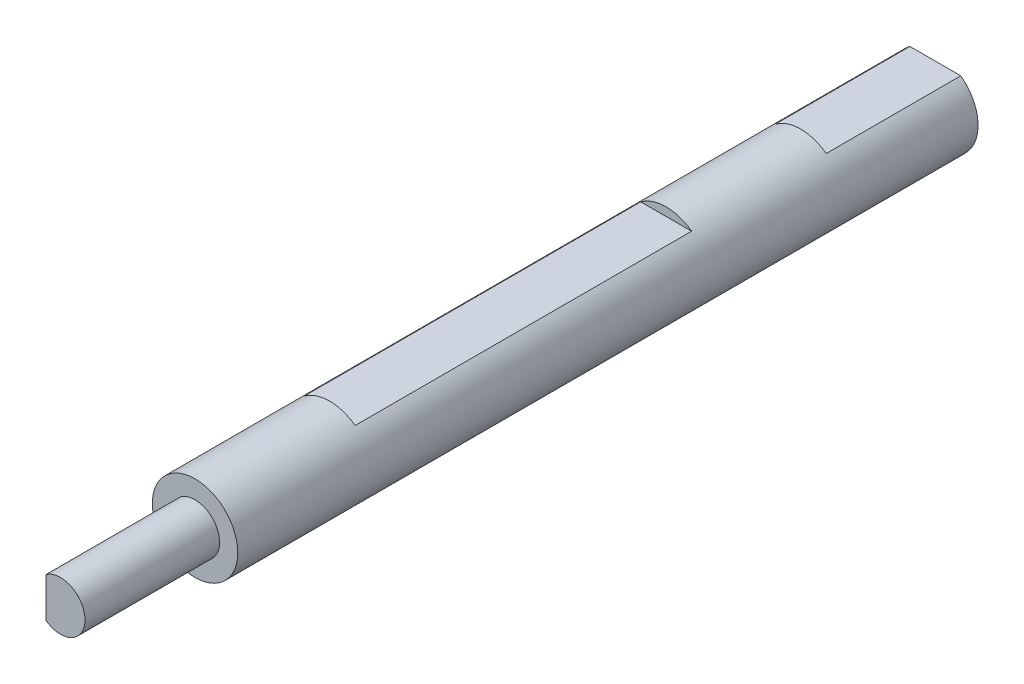
SolidWorks part; units mm, degrees
ref_plane "Front Plane" through (0, 0, 0) normal (0, 0, 1) x (1, 0, 0)
ref_plane "Top Plane" through (0, 0, 0) normal (0, 1, 0) x (1, 0, 0)
ref_plane "Right Plane" through (0, 0, 0) normal (1, 0, 0) x (0, 0, -1)
sketch "Sketch1" plane through (0, 0, 0) normal (0, 0, 1) x (1, 0, 0)
  circle A0 centre (0, 0) radius 3.175
  dimension "D1" = 6.35
extrude "Boss-Extrude1" add sketch "Sketch1" along normal blind 65
sketch "Sketch2" plane through (0, 0, 0) normal (0, 0, -1) x (-1, 0, 0)
  line L0 (-1.8916, 2.55) -> (1.8916, 2.55)
  line L1 (-1.8916, -2.55) -> (1.8916, -2.55)
  line L2 (0, 2.55) -> (0, -2.55) construction
  circle A0 centre (0, 0) radius 3.175 construction
  arc A1 (-1.8916, -2.55) -> (1.8916, -2.55) centre (0, 0) ccw
  arc A2 (1.8916, 2.55) -> (-1.8916, 2.55) centre (0, 0) ccw
  point P4 (0, 0)
  dimension "D1" = 5.1
extrude "Cut-Extrude1" cut sketch "Sketch2" against normal blind 10
ref_plane "Plane1" through (0, 0, 20) normal (0, 0, -1) x (-1, 0, 0)
sketch "Sketch3" plane through (0, 0, 20) normal (0, 0, -1) x (-1, 0, 0)
  line L0 (-1.8916, 2.55) -> (1.8916, 2.55)
  arc A0 (1.8916, 2.55) -> (-1.8916, 2.55) centre (0, 0) ccw
  arc A1 (1.8916, -2.55) -> (1.8916, 2.55) centre (0, 0) ccw construction
extrude "Cut-Extrude2" cut sketch "Sketch3" against normal blind 25
sketch "Sketch4" plane through (0, 0, 65) normal (0, 0, 1) x (1, 0, 0)
  line L0 (-1.073, -1.4787) -> (-1.073, 1.4787)
  line L1 (1.827, -1.5137) -> (1.827, 1.8154) construction
  arc A0 (-1.073, -1.4787) -> (-1.073, 1.4787) centre (0, 0) ccw
  circle A1 centre (0, 0) radius 3.175
  circle A2 centre (0, 0) radius 3.175 construction
  dimension "D1" = 3.654
  dimension "D2" = 2.9
extrude "Cut-Extrude3" cut sketch "Sketch4" against normal blind 10
